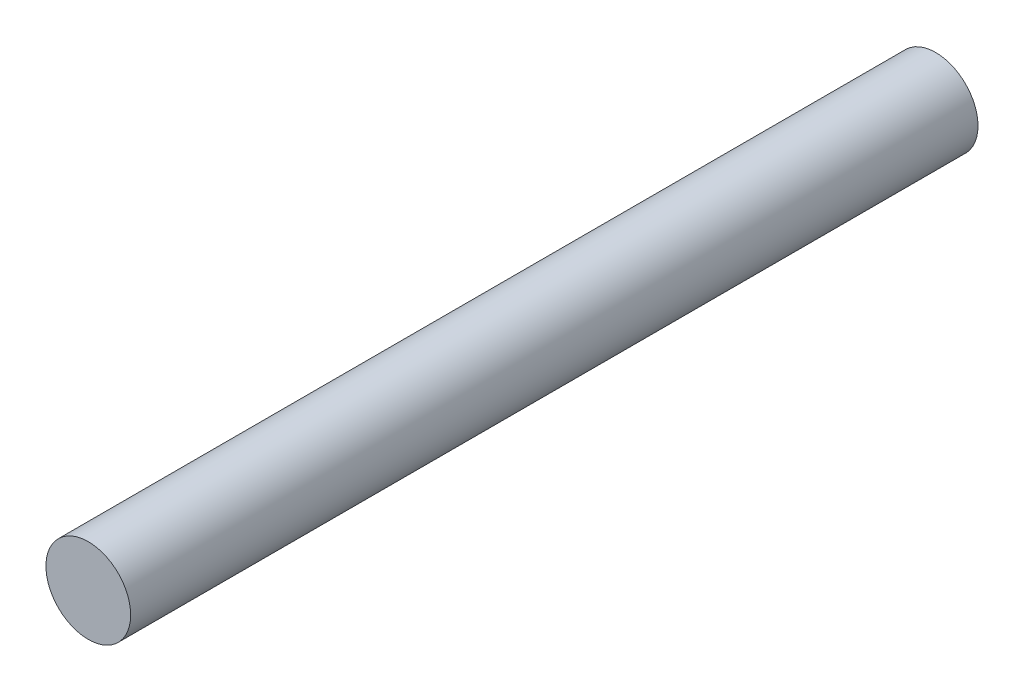
SolidWorks part; units mm, degrees
ref_plane "Plan de face" through (0, 0, 0) normal (0, 0, 1) x (1, 0, 0)
ref_plane "Plan de dessus" through (0, 0, 0) normal (0, 1, 0) x (1, 0, 0)
ref_plane "Plan de droite" through (0, 0, 0) normal (1, 0, 0) x (0, 0, -1)
sketch "Esquisse1" plane through (0, 0, 0) normal (0, 0, 1) x (1, 0, 0)
  circle A0 centre (0, 0) radius 25
  dimension "D1" = 50
extrude "Boss.-Extru.1" add sketch "Esquisse1" along normal blind 500
